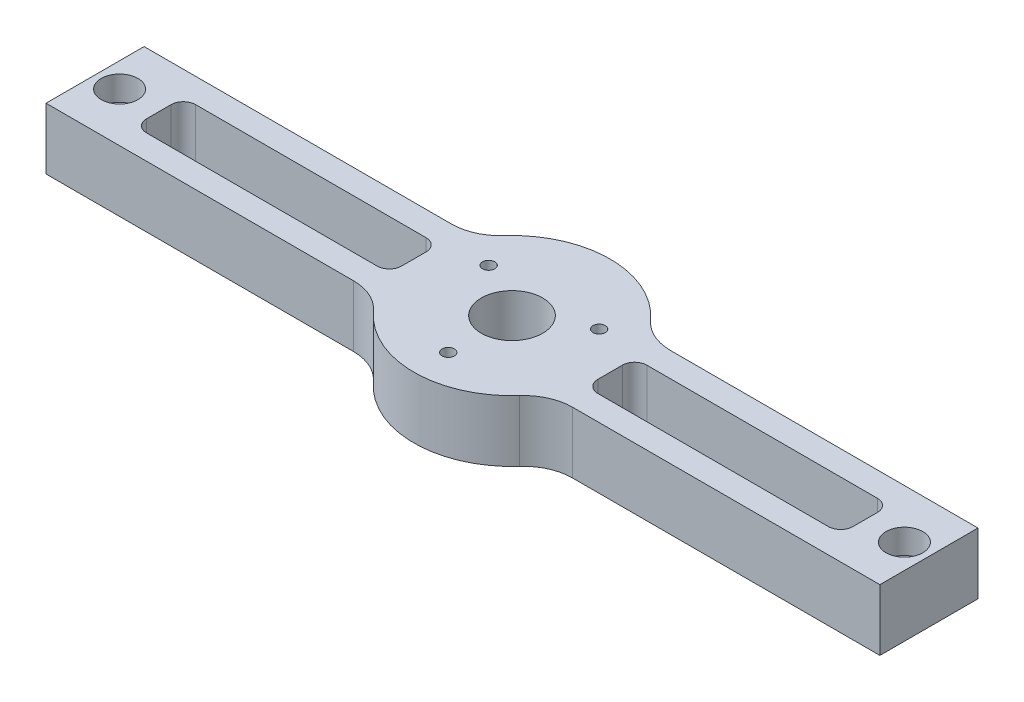
SolidWorks part; units mm, degrees
material "6061-T6 (SS)"
ref_plane "Front Plane" through (0, 0, 0) normal (0, 0, 1) x (1, 0, 0)
ref_plane "Top Plane" through (0, 0, 0) normal (0, 1, 0) x (1, 0, 0)
ref_plane "Right Plane" through (0, 0, 0) normal (1, 0, 0) x (0, 0, -1)
sketch "Sketch2" plane through (0, 0, 0) normal (0, 1, 0) x (1, 0, 0)
  line L0 (-21.997, 0) -> (0, 0) construction
  line L1 (-107.95, -25.4) -> (-21.997, -25.4)
  line L2 (-107.95, -25.4) -> (-107.95, 0)
  line L3 (-107.95, 0) -> (-21.997, 0)
  line L4 (-21.997, -25.4) -> (-21.997, 0)
  line L5 (21.997, -25.4) -> (107.95, -25.4)
  line L6 (21.997, -25.4) -> (21.997, 0)
  line L7 (21.997, 0) -> (107.95, 0)
  line L8 (107.95, -25.4) -> (107.95, 0)
  line L9 (0, 0) -> (21.997, 0) construction
  circle A0 centre (0, -12.7) radius 7.9375
  circle A1 centre (0, -12.7) radius 25.4
  point P13 (107.95, -12.7)
  dimension "D3" = 215.9
  dimension "D4" = 15.875
  dimension "D5" = 50.8
  dimension "D1" = 25.4
  dimension "D2" = 25.4
extrude "Boss-Extrude1" add sketch "Sketch2" along normal blind 15.875 contours A1 L3 L2 L1 | L4 A1 | L6 A1 L4 A0 | L6 A1 | A1 L5 L8 L7
fillet "Fillet1" radius 12.7 4 edges at (21.997, 7.9375, 0) (21.997, 7.9375, 25.4) (-21.997, 7.9375, 25.4) (-21.997, 7.9375, 0)
sketch "Sketch3" plane through (0, 0, 0) normal (0, -1, 0) x (1, 0, 0)
  circle A0 centre (0, 12.7) radius 22.225
  dimension "D1" = 44.45
extrude "Cut-Extrude1" cut sketch "Sketch3" against normal blind 3.175
sketch "Sketch4" plane through (0, 15.875, 0) normal (0, 1, 0) x (1, 0, 0)
  line L0 (-107.95, -25.4) -> (-107.95, 0) construction
  line L1 (107.95, -25.4) -> (107.95, 0) construction
  circle A0 centre (-101.6, -12.7) radius 4.7625
  circle A1 centre (101.6, -12.7) radius 4.7625
  point P4 (-107.95, -12.7)
  point P5 (107.95, -12.7)
  dimension "D1" = 9.525
  dimension "D2" = 9.525
  dimension "D3" = 6.35
  dimension "D4" = 6.35
extrude "Cut-Extrude2" cut sketch "Sketch4" against normal blind 6.35
sketch "Sketch5" plane through (0, 9.525, 0) normal (0, 1, 0) x (1, 0, 0)
  circle A0 centre (-101.6, -12.7) radius 3.175
  circle A1 centre (101.6, -12.7) radius 3.175
  dimension "D1" = 6.35
  dimension "D2" = 6.35
extrude "Cut-Extrude3" cut sketch "Sketch5" against normal through all
sketch "Sketch6" plane through (0, 3.175, 0) normal (0, -1, 0) x (1, 0, 0)
  circle A0 centre (0, 29.21) radius 1.5875
  circle A1 centre (0, 12.7) radius 7.9375 construction
  circle A2 centre (0, 12.7) radius 7.9375 construction
  circle A3 centre (14.2981, 4.445) radius 1.5875
  circle A4 centre (-14.2981, 4.445) radius 1.5875
  dimension "D2" = 3.175
  dimension "D1" = 16.51
  dimension "D3" = 3
extrude "Cut-Extrude4" cut sketch "Sketch6" against normal through all
sketch "Sketch7" plane through (0, 15.875, 0) normal (0, 1, 0) x (1, 0, 0)
  line L0 (-107.95, 0) -> (-28.3981, 0) construction
  line L1 (-91.44, -19.05) -> (-25.4, -19.05)
  line L2 (-91.44, -19.05) -> (-91.44, -6.35)
  line L3 (-91.44, -6.35) -> (-25.4, -6.35)
  line L4 (-25.4, -19.05) -> (-25.4, -6.35)
  line L5 (25.4, -19.05) -> (91.44, -19.05)
  line L6 (25.4, -19.05) -> (25.4, -6.35)
  line L7 (25.4, -6.35) -> (91.44, -6.35)
  line L8 (91.44, -19.05) -> (91.44, -6.35)
  line L9 (-107.95, -25.4) -> (-28.3981, -25.4) construction
  circle A0 centre (-101.6, -12.7) radius 4.7625 construction
  circle A1 centre (101.6, -12.7) radius 4.7625 construction
  dimension "D3" = 10.16
  dimension "D1" = 6.35
  dimension "D2" = 6.35
  dimension "D4" = 50.8
  dimension "D5" = 10.16
extrude "Cut-Extrude5" cut sketch "Sketch7" against normal through all
fillet "Fillet2" radius 3.175 8 edges at (25.4, 7.9375, 6.35) (25.4, 7.9375, 19.05) (91.44, 7.9375, 19.05) (91.44, 7.9375, 6.35) (-25.4, 7.9375, 6.35) (-25.4, 7.9375, 19.05) (-91.44, 7.9375, 19.05) (-91.44, 7.9375, 6.35)
